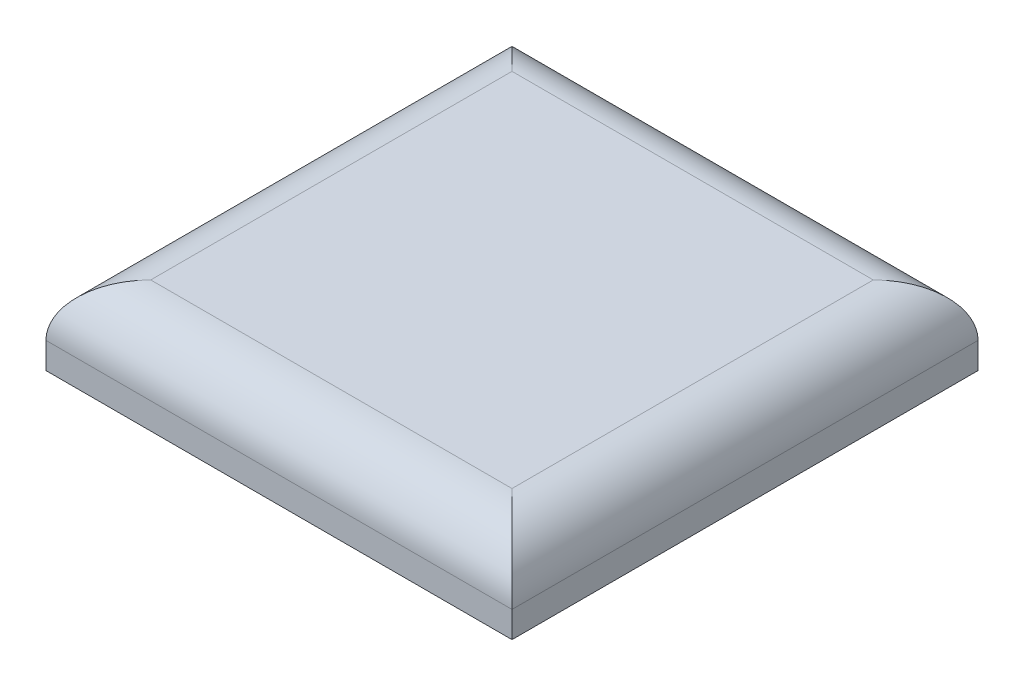
SolidWorks part; units mm, degrees
ref_plane "Спереди" through (0, 0, 0) normal (0, 0, 1) x (1, 0, 0)
ref_plane "Сверху" through (0, 0, 0) normal (0, 1, 0) x (1, 0, 0)
ref_plane "Справа" through (0, 0, 0) normal (1, 0, 0) x (0, 0, -1)
sketch "Эскиз1" plane through (0, 0, 0) normal (0, 1, 0) x (1, 0, 0)
  line L1 (-8.9, -8.9) -> (8.9, -8.9)
  line L2 (-8.9, -8.9) -> (-8.9, 8.9)
  line L3 (-8.9, 8.9) -> (8.9, 8.9)
  line L4 (8.9, -8.9) -> (8.9, 8.9)
  line L5 (-8.9, -8.9) -> (8.9, 8.9) construction
  line L6 (-8.9, 8.9) -> (8.9, -8.9) construction
  point P0 (0, 0)
extrude "Бобышка-Вытянуть1" add sketch "Эскиз1" along normal blind 3
fillet "Скругление1" radius 2 4 edges at (-8.9, 3, 0) (0, 3, 8.9) (8.9, 3, 0) (0, 3, -8.9)
